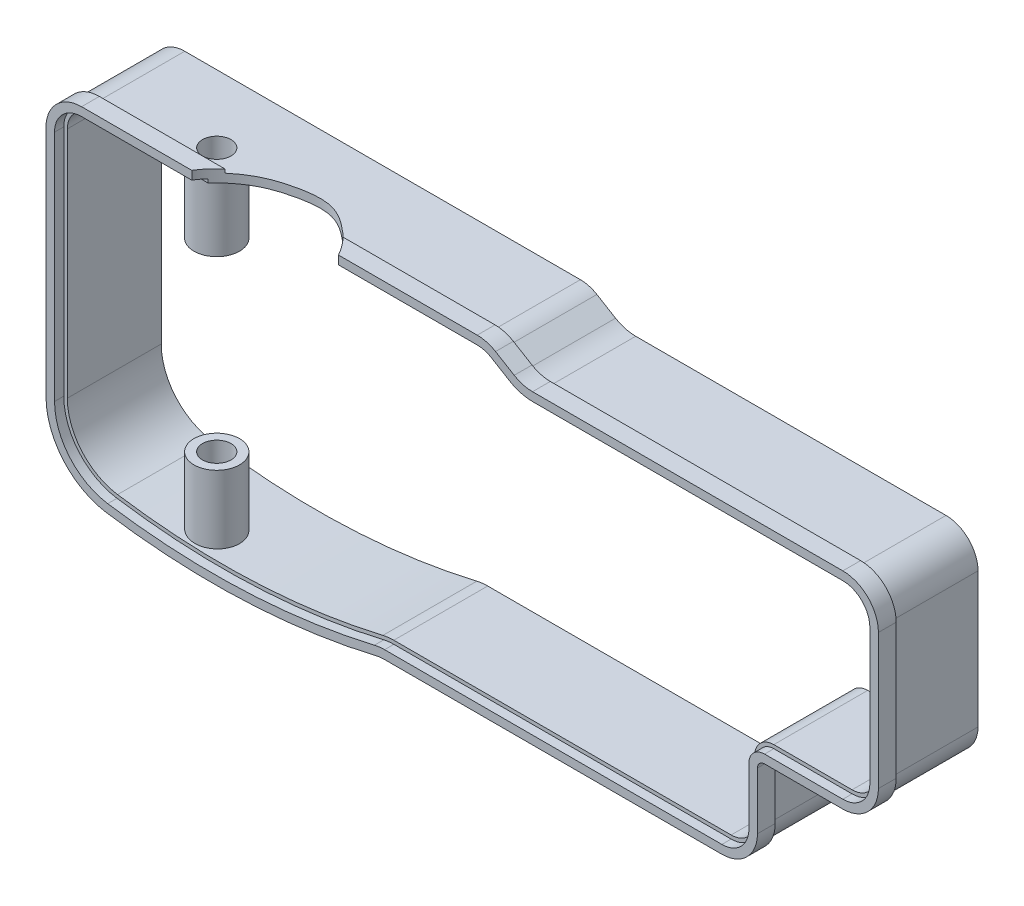
SolidWorks part; units mm, degrees
ref_plane "前视基准面" through (0, 0, 0) normal (0, 0, 1) x (1, 0, 0)
ref_plane "上视基准面" through (0, 0, 0) normal (0, 1, 0) x (1, 0, 0)
ref_plane "右视基准面" through (0, 0, 0) normal (1, 0, 0) x (0, 0, -1)
sketch "草图1" plane through (0, 0, 0) normal (0, 0, 1) x (1, 0, 0)
  line L0 (17, 0) -> (17, 14)
  line L1 (17, 0) -> (70, 0)
  line L2 (0, 14) -> (0, 43)
  line L3 (0, 43) -> (50, 43)
  line L4 (117, 0) -> (117, 43)
  line L5 (17, 14) -> (0, 14)
  line L6 (50, 43) -> (55, 46)
  line L7 (55, 46) -> (117, 46)
  line L8 (117, 46) -> (117, 43)
  arc A0 (70, 0) -> (117, 0) centre (93.5, 97.1995) ccw
  dimension "D4" = 100
  dimension "D2" = 117
  dimension "D5" = 17
  dimension "D6" = 14
  dimension "D7" = 46
  dimension "D8" = 50
  dimension "D9" = 62
extrude "凸台-拉伸1" add sketch "草图1" along normal blind 2.5
fillet "圆角1" radius 5 4 edges at (17, 0, 1.25) (0, 14, 1.25) (0, 43, 1.25) (117, 46, 1.25)
fillet "圆角2" radius 10 1 edges at (117, 0, 1.25)
fillet "圆角3" radius 5 3 edges at (70, 0, 1.25) (50, 43, 1.25) (55, 46, 1.25)
fillet "圆角4" radius 1 1 edges at (17, 14, 1.25)
sketch "草图2" plane through (0, 0, 0) normal (0, 0, -1) x (-1, 0, 0)
  line L16 (-51.4448, 43.2838) -> (-54.0697, 44.8587)
  line L17 (-56.3849, 45.5) -> (-112, 45.5)
  line L18 (-116.5, 41) -> (-116.5, 8.2178)
  line L19 (-69.4115, 0.5) -> (-22, 0.5)
  line L20 (-17.5, 5) -> (-17.5, 13)
  line L21 (-16, 14.5) -> (-5, 14.5)
  line L22 (-0.5, 19) -> (-0.5, 38)
  line L23 (-5, 42.5) -> (-48.6151, 42.5)
  line L24 (-51.4448, 43.2838) -> (-54.0697, 44.8587)
  line L25 (-56.3849, 45.5) -> (-112, 45.5)
  line L26 (-116.5, 41) -> (-116.5, 8.2178)
  line L27 (-69.4115, 0.5) -> (-22, 0.5)
  line L28 (-17.5, 5) -> (-17.5, 13)
  line L29 (-16, 14.5) -> (-5, 14.5)
  line L30 (-0.5, 19) -> (-0.5, 38)
  line L31 (-5, 42.5) -> (-48.6151, 42.5)
  arc A20 (-54.0697, 44.8587) -> (-56.3849, 45.5) centre (-56.3849, 41) ccw
  arc A21 (-112, 45.5) -> (-116.5, 41) centre (-112, 41) ccw
  arc A22 (-116.5, 8.2178) -> (-108.425, -1.1747) centre (-107, 8.2178) ccw
  arc A23 (-108.425, -1.1747) -> (-70.6733, 0.3533) centre (-93.5, 97.1995) ccw
  arc A24 (-69.4115, 0.5) -> (-70.6733, 0.3533) centre (-69.4115, -5) ccw
  arc A25 (-22, 0.5) -> (-17.5, 5) centre (-22, 5) ccw
  arc A26 (-16, 14.5) -> (-17.5, 13) centre (-16, 13) ccw
  arc A27 (-5, 14.5) -> (-0.5, 19) centre (-5, 19) ccw
  arc A28 (-0.5, 38) -> (-5, 42.5) centre (-5, 38) ccw
  arc A29 (-51.4448, 43.2838) -> (-48.6151, 42.5) centre (-48.6151, 48) ccw
  arc A30 (-54.0697, 44.8587) -> (-56.3849, 45.5) centre (-56.3849, 41) ccw
  arc A31 (-112, 45.5) -> (-116.5, 41) centre (-112, 41) ccw
  arc A32 (-116.5, 8.2178) -> (-108.425, -1.1747) centre (-107, 8.2178) ccw
  arc A33 (-108.425, -1.1747) -> (-70.6733, 0.3533) centre (-93.5, 97.1995) ccw
  arc A34 (-69.4115, 0.5) -> (-70.6733, 0.3533) centre (-69.4115, -5) ccw
  arc A35 (-22, 0.5) -> (-17.5, 5) centre (-22, 5) ccw
  arc A36 (-16, 14.5) -> (-17.5, 13) centre (-16, 13) ccw
  arc A37 (-5, 14.5) -> (-0.5, 19) centre (-5, 19) ccw
  arc A38 (-0.5, 38) -> (-5, 42.5) centre (-5, 38) ccw
  arc A39 (-51.4448, 43.2838) -> (-48.6151, 42.5) centre (-48.6151, 48) ccw
  dimension "D1" = 0.5
extrude "凸台-拉伸2" add sketch "草图2" along normal blind 12
sketch "草图3" plane through (0, 45.5, 0) normal (0, 1, 0) x (1, 0, 0)
  line L0 (112, -2.5) -> (56.3849, -2.5) construction
  line L1 (117, 0) -> (117, -2.5) construction
  circle A0 centre (98, 2.5) radius 2
  dimension "D1" = 4
  dimension "D3" = 19
  dimension "D2" = 5
extrude "切除-拉伸1" cut sketch "草图3" against normal through all
shell "抽壳1" thickness 1.2
sketch "草图4" plane through (0, 0, 1.3) normal (0, 0, -1) x (-1, 0, 0)
  line L8 (-56.3849, 44.8) -> (-112, 44.8)
  line L9 (-115.8, 41) -> (-115.8, 8.2178)
  line L10 (-69.4115, 1.2) -> (-22, 1.2)
  line L11 (-18.2, 5) -> (-18.2, 13)
  line L12 (-16, 15.2) -> (-5, 15.2)
  line L13 (-1.2, 19) -> (-1.2, 38)
  line L14 (-5, 41.8) -> (-48.6151, 41.8)
  line L15 (-51.805, 42.6835) -> (-54.4298, 44.2585)
  line L16 (-56.3849, 44.8) -> (-112, 44.8)
  line L17 (-115.8, 41) -> (-115.8, 8.2178)
  line L18 (-69.4115, 1.2) -> (-22, 1.2)
  line L19 (-18.2, 5) -> (-18.2, 13)
  line L20 (-16, 15.2) -> (-5, 15.2)
  line L21 (-1.2, 19) -> (-1.2, 38)
  line L22 (-5, 41.8) -> (-48.6151, 41.8)
  line L23 (-51.805, 42.6835) -> (-54.4298, 44.2585)
  arc A10 (-112, 44.8) -> (-115.8, 41) centre (-112, 41) ccw
  arc A11 (-115.8, 8.2178) -> (-108.32, -0.4826) centre (-107, 8.2178) ccw
  arc A12 (-108.32, -0.4826) -> (-70.8339, 1.0346) centre (-93.5, 97.1995) ccw
  arc A13 (-69.4115, 1.2) -> (-70.8339, 1.0346) centre (-69.4115, -5) ccw
  arc A14 (-22, 1.2) -> (-18.2, 5) centre (-22, 5) ccw
  arc A15 (-16, 15.2) -> (-18.2, 13) centre (-16, 13) ccw
  arc A16 (-5, 15.2) -> (-1.2, 19) centre (-5, 19) ccw
  arc A17 (-1.2, 38) -> (-5, 41.8) centre (-5, 38) ccw
  arc A18 (-51.805, 42.6835) -> (-48.6151, 41.8) centre (-48.6151, 48) ccw
  arc A19 (-54.4298, 44.2585) -> (-56.3849, 44.8) centre (-56.3849, 41) ccw
  arc A20 (-112, 44.8) -> (-115.8, 41) centre (-112, 41) ccw
  arc A21 (-115.8, 8.2178) -> (-108.32, -0.4826) centre (-107, 8.2178) ccw
  arc A22 (-108.32, -0.4826) -> (-70.8339, 1.0346) centre (-93.5, 97.1995) ccw
  arc A23 (-69.4115, 1.2) -> (-70.8339, 1.0346) centre (-69.4115, -5) ccw
  arc A24 (-22, 1.2) -> (-18.2, 5) centre (-22, 5) ccw
  arc A25 (-16, 15.2) -> (-18.2, 13) centre (-16, 13) ccw
  arc A26 (-5, 15.2) -> (-1.2, 19) centre (-5, 19) ccw
  arc A27 (-1.2, 38) -> (-5, 41.8) centre (-5, 38) ccw
  arc A28 (-51.805, 42.6835) -> (-48.6151, 41.8) centre (-48.6151, 48) ccw
  arc A29 (-54.4298, 44.2585) -> (-56.3849, 44.8) centre (-56.3849, 41) ccw
  dimension "D1" = 0
extrude "切除-拉伸2" cut sketch "草图4" against normal through all
sketch "草图5" plane through (0, 0, 2.5) normal (0, 0, 1) x (1, 0, 0)
  line L0 (112, 46) -> (56.3849, 46) construction
  line L1 (79.1953, 34.5) -> (109.1042, 34.5)
  line L2 (79.1953, 34.5) -> (79.1953, 8.5)
  line L3 (79.1953, 8.5) -> (109.1042, 8.5)
  line L4 (109.1042, 34.5) -> (109.1042, 8.5)
  dimension "D1" = 11.5
  dimension "D2" = 26
extrude "切除-拉伸3" cut sketch "草图5" against normal blind 12
sketch "草图6" plane through (0, 46, 0) normal (0, 1, 0) x (1, 0, 0)
  spline S0 degree 3 poles (71.0943, -10.0246) (103.8497, -9.3957) (93.2311, 1.4451) (88.1301, 3.3043) (82.9063, 4.0739) (79.3274, 1.5601) (76.9251, -0.689) (71.0943, -10.0246) (103.8497, -9.3957) (93.2311, 1.4451) knots -0.572635 -0.506756 -0.437414 0 0.133194 0.239246 0.354041 0.427365 0.493244 0.562586 1 1.133194 1.239246 1.354041 only from (96.9964, -4.0542) to (96.9964, -4.0542)
extrude "切除-拉伸4" cut sketch "草图6" against normal blind 25
mirror "镜向1" about plane through (0, 14, 2.5) normal (1, 0, 0) of bodies 118
ref_plane "基准面1" through (0, 0, 0) normal (-1, 0, 0) x (0, 0, 1)
sketch "草图7" plane through (0, 0, 0) normal (-1, 0, 0) x (0, 0, 1)
  line L1 (-17.5401, 47.3846) -> (7.2869, 47.3846)
  line L2 (-17.5401, 47.3846) -> (-17.5401, -5.8708)
  line L3 (-17.5401, -5.8708) -> (7.2869, -5.8708)
  line L4 (7.2869, 47.3846) -> (7.2869, -5.8708)
extrude "切除-拉伸5" cut sketch "草图7" against normal blind 140
